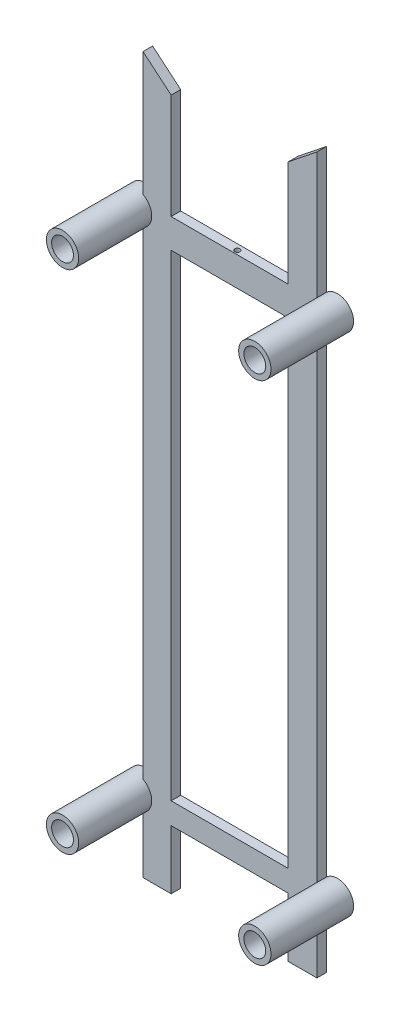
SolidWorks part; units mm, degrees
ref_plane "Front Plane" through (0, 0, 0) normal (0, 0, 1) x (1, 0, 0)
ref_plane "Top Plane" through (0, 0, 0) normal (0, 1, 0) x (1, 0, 0)
ref_plane "Right Plane" through (0, 0, 0) normal (1, 0, 0) x (0, 0, -1)
sketch "Sketch1" plane through (0, 0, 427.0141) normal (0, 0, 1) x (1, 0, 0)
  circle A0 centre (1173.6392, -317.2016) radius 38.7717
  circle A1 centre (1173.6392, -317.2016) radius 57.281
  circle A2 centre (491.7651, -317.2016) radius 38.7717
  circle A3 centre (491.7651, -317.2016) radius 57.281
  circle A4 centre (491.7651, -2112.8608) radius 38.7717
  circle A5 centre (491.7651, -2112.8608) radius 57.281
  circle A6 centre (1173.6392, -2112.8608) radius 38.7717
  circle A7 centre (1173.6392, -2112.8608) radius 57.281
  dimension "D1" = 114.562
  dimension "D2" = 114.562
  dimension "D3" = 114.562
  dimension "D4" = 114.562
  dimension "D5" = 77.5434
  dimension "D6" = 77.5434
  dimension "D7" = 77.5434
  dimension "D8" = 77.5434
extrude "Boss-Extrude1" add sketch "Sketch1" along normal blind 293 from offset 600
sketch "Sketch2" plane through (0, 0, 1027.0141) normal (0, 0, -1) x (-1, 0, 0)
  line L0 (-1134.8675, 91.6172) -> (-1134.8675, 172.7652)
  line L1 (-1134.8675, -2363.9974) -> (-1033.1667, -2363.9974)
  line L2 (-1134.8675, -2363.9974) -> (-1134.8675, 91.6172)
  line L4 (-1033.1667, -2363.9974) -> (-1033.1667, 91.6172)
  line L5 (-518.1595, -2363.9974) -> (-617.8837, -2363.9974)
  line L6 (-518.1595, -2363.9974) -> (-518.1595, 88.9058)
  line L8 (-617.8837, -2363.9974) -> (-617.8837, 88.9058)
  line L9 (-1134.8675, -2154.5063) -> (-518.1595, -2154.5063)
  line L10 (-1134.8675, -2154.5063) -> (-1134.8675, -2078.311)
  line L11 (-1134.8675, -2078.311) -> (-518.1595, -2078.311)
  line L12 (-518.1595, -2154.5063) -> (-518.1595, -2078.311)
  line L13 (-1134.8675, -387.5825) -> (-518.1595, -387.5825)
  line L14 (-1134.8675, -387.5825) -> (-1134.8675, -284.0952)
  line L15 (-1134.8675, -284.0952) -> (-518.1595, -284.0952)
  line L16 (-518.1595, -387.5825) -> (-518.1595, -284.0952)
  line L17 (-1134.8675, 769) -> (-1134.8675, -2363.9974) construction
  line L18 (-1134.8675, 172.7652) -> (-1033.1667, 91.6172)
  line L19 (-518.1595, 88.9058) -> (-518.1595, 172.7652)
  line L20 (-518.1595, 769) -> (-518.1595, -2363.9974) construction
  line L21 (-518.1595, 172.7652) -> (-617.8837, 88.9058)
  circle A0 centre (-833.9306, -1197.1664) radius 1304.0928 construction
extrude "Boss-Extrude2" add sketch "Sketch2" against normal blind 34
sketch "Sketch6" plane through (0, -284.0952, 0) normal (0, 1, 0) x (1, 0, 0)
  circle A0 centre (838.8984, -1047.1552) radius 9.3137
extrude "Cut-Extrude3" cut sketch "Sketch6" against normal blind 126
